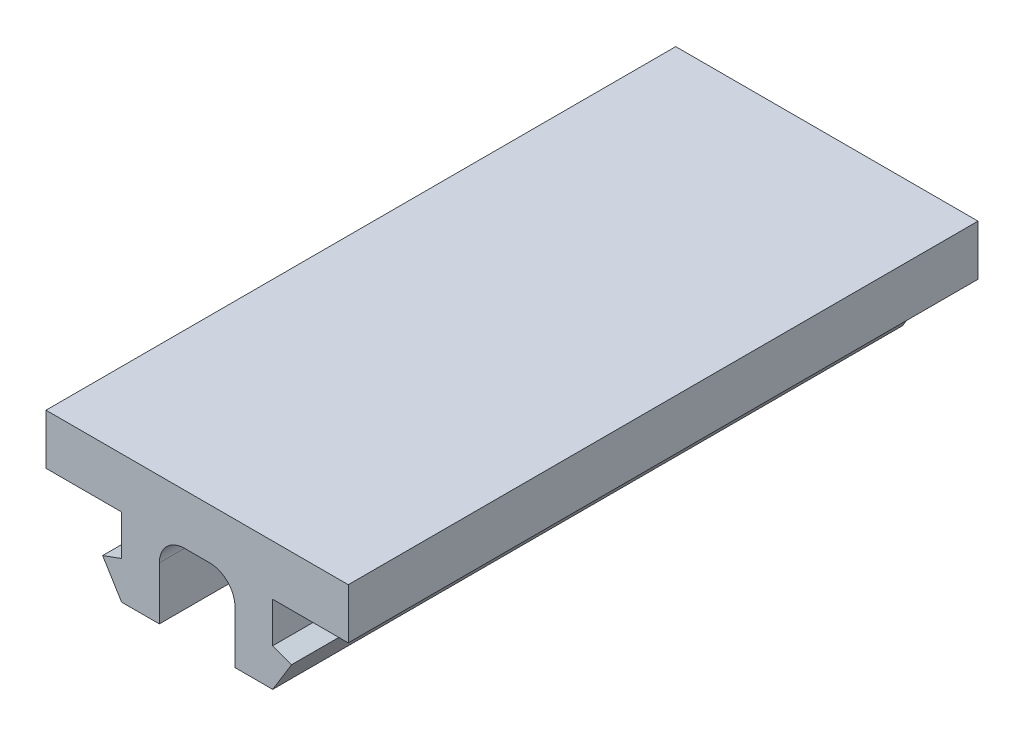
SolidWorks part; units mm, degrees
ref_plane "Front Plane" through (0, 0, 0) normal (0, 0, 1) x (1, 0, 0)
ref_plane "Top Plane" through (0, 0, 0) normal (0, 1, 0) x (1, 0, 0)
ref_plane "Right Plane" through (0, 0, 0) normal (1, 0, 0) x (0, 0, -1)
sketch "Sketch1" plane through (0, 0, 0) normal (0, 0, 1) x (1, 0, 0)
  line L0 (0, 0) -> (12, 0)
  line L1 (12, 0) -> (12, -2)
  line L2 (12, -2) -> (9, -2)
  line L3 (9, -2) -> (9, -3.6)
  line L4 (9, -3.6) -> (9.7518, -3.8736)
  line L5 (9.7518, -3.8736) -> (9, -5.1)
  line L6 (9, -5.1) -> (7.5, -5.1)
  line L7 (3, -5.1) -> (2.2482, -3.8736)
  line L8 (2.2482, -3.8736) -> (3, -3.6)
  line L9 (3, -3.6) -> (3, -2)
  line L10 (3, -2) -> (0, -2)
  line L11 (0, -2) -> (0, 0)
  line L12 (4.5, -5.1) -> (3, -5.1)
  line L14 (4.5, -5.1) -> (4.5, -3)
  line L15 (5.5, -2) -> (6.5, -2)
  line L16 (7.5, -5.1) -> (7.5, -3)
  arc A0 (5.5, -2) -> (4.5, -3) centre (5.5, -3) ccw
  arc A1 (7.5, -3) -> (6.5, -2) centre (6.5, -3) ccw
  point P0 (6, -2)
  point P12 (6, 0)
  point P15 (2.3508, -3.8239)
  point P22 (4.5, -2)
  dimension "D9" = 1
  dimension "D1" = 2
  dimension "D2" = 12
  dimension "D3" = 6
  dimension "D4" = 110
  dimension "D5" = 0.8
  dimension "D6" = 1.5
  dimension "D7" = 1.6
  dimension "D8" = 3.1
extrude "Boss-Extrude1" add sketch "Sketch1" along normal blind 25
